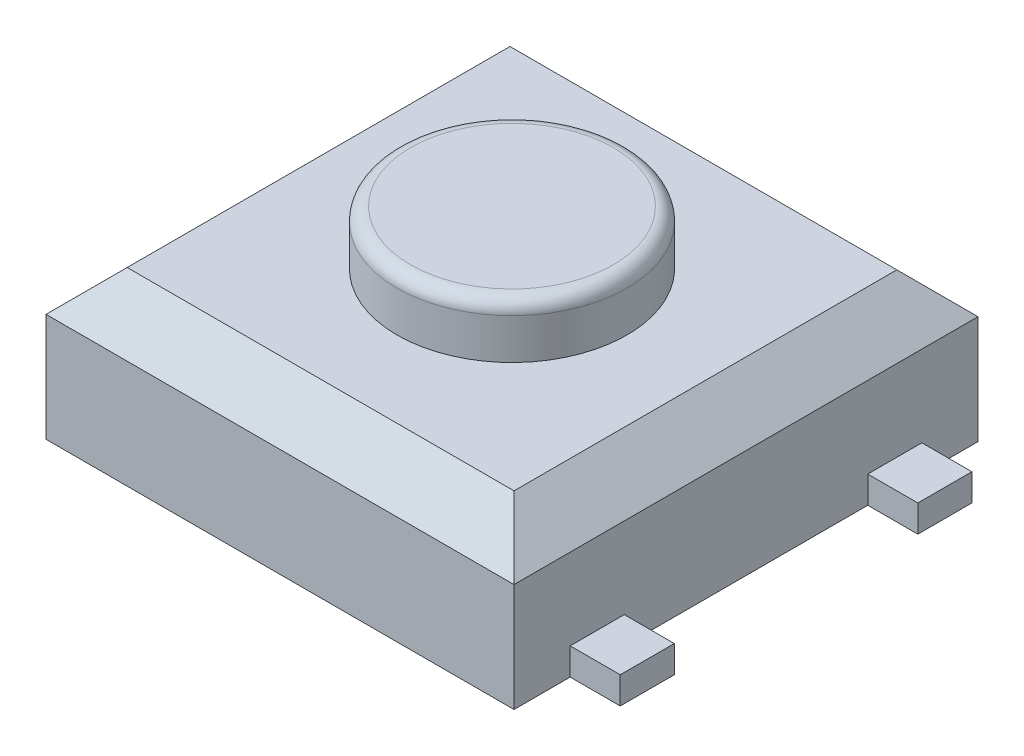
SolidWorks part; units mm, degrees
ref_plane "Front Plane" through (0, 0, 0) normal (0, 0, 1) x (1, 0, 0)
ref_plane "Top Plane" through (0, 0, 0) normal (0, 1, 0) x (1, 0, 0)
ref_plane "Right Plane" through (0, 0, 0) normal (1, 0, 0) x (0, 0, -1)
sketch "Sketch1" plane through (0, 0, 0) normal (0, 1, 0) x (1, 0, 0)
  line L1 (-1.73, -1.715) -> (1.73, -1.715)
  line L2 (-1.73, -1.715) -> (-1.73, 1.715)
  line L3 (-1.73, 1.715) -> (1.73, 1.715)
  line L4 (1.73, -1.715) -> (1.73, 1.715)
  line L5 (-1.73, -1.715) -> (1.73, 1.715) construction
  line L6 (-1.73, 1.715) -> (1.73, -1.715) construction
  line L7 (-1.73, 1.3) -> (-2.1, 1.3)
  line L8 (-1.73, 1.3) -> (-1.73, 0.9)
  line L9 (-1.73, 0.9) -> (-2.1, 0.9)
  line L10 (-2.1, 1.3) -> (-2.1, 0.9)
  line L11 (-1.73, -0.9) -> (-2.1, -0.9)
  line L12 (-1.73, -0.9) -> (-1.73, -1.3)
  line L13 (-1.73, -1.3) -> (-2.1, -1.3)
  line L14 (-2.1, -0.9) -> (-2.1, -1.3)
  line L15 (1.73, -0.9) -> (2.1, -0.9)
  line L16 (1.73, -0.9) -> (1.73, -1.3)
  line L17 (1.73, -1.3) -> (2.1, -1.3)
  line L18 (2.1, -0.9) -> (2.1, -1.3)
  line L19 (1.73, 1.3) -> (2.1, 1.3)
  line L20 (1.73, 1.3) -> (1.73, 0.9)
  line L21 (1.73, 0.9) -> (2.1, 0.9)
  line L22 (2.1, 1.3) -> (2.1, 0.9)
  point P0 (0, 0)
  dimension "D1" = 3.43
  dimension "D2" = 3.46
  dimension "D3" = 4.2
  dimension "D4" = 0.4
  dimension "D5" = 0.9
  dimension "D6" = 2.2
extrude "Boss-Extrude1" add sketch "Sketch1" along normal blind 0.2 contours L1 L4 L3 L2 | L18 L15 L4 L17 | L11 L14 L13 L2 | L7 L10 L9 L2 | L22 L21 L20 L19
sketch "Sketch2" plane through (0, 0.2, 0) normal (0, 1, 0) x (1, 0, 0)
  line L1 (-1.73, 1.715) -> (1.73, 1.715)
  line L2 (-1.73, 1.715) -> (-1.73, -1.715)
  line L3 (-1.73, -1.715) -> (1.73, -1.715)
  line L4 (1.73, 1.715) -> (1.73, -1.715)
extrude "Boss-Extrude2" add sketch "Sketch2" along normal blind 0.9
chamfer "Chamfer1" distance 0.3 angle 45 4 edges at (0, 1.1, -1.715) (1.73, 1.1, 0) (0, 1.1, 1.715) (-1.73, 1.1, 0)
sketch "Sketch3" plane through (0, 1.1, 0) normal (0, 1, 0) x (1, 0, 0)
  circle A0 centre (0, 0) radius 0.85
  dimension "D1" = 1.7
extrude "Boss-Extrude3" add sketch "Sketch3" along normal blind 0.4
fillet "Fillet1" radius 0.1 1 edges at (0, 1.5, 0.85)
